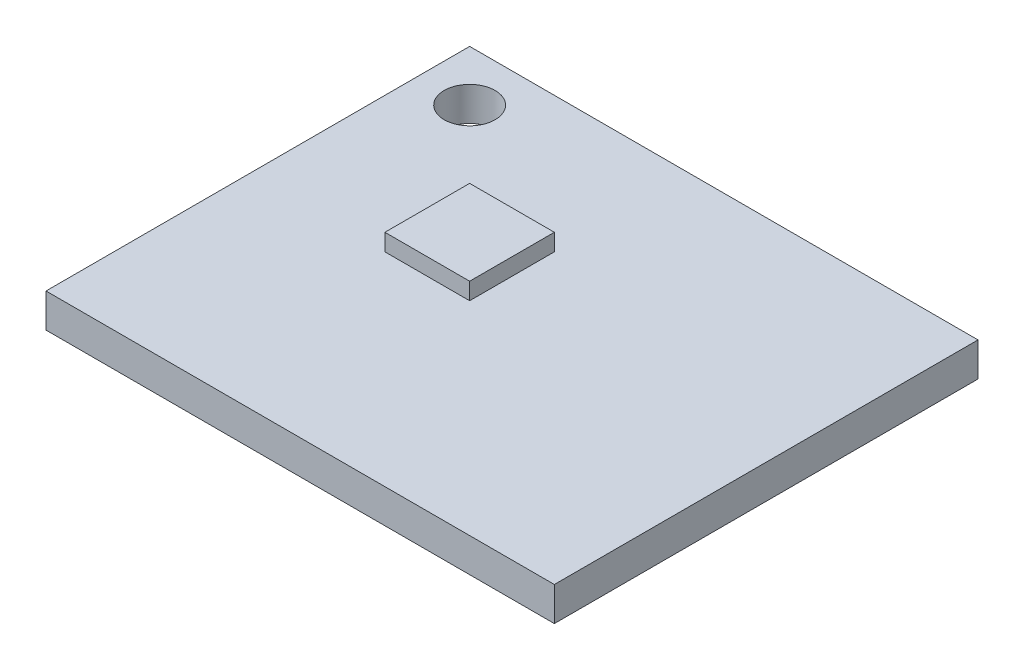
SolidWorks part; units mm, degrees
ref_plane "Front Plane" through (0, 0, 0) normal (0, 0, 1) x (1, 0, 0)
ref_plane "Top Plane" through (0, 0, 0) normal (0, 1, 0) x (1, 0, 0)
ref_plane "Right Plane" through (0, 0, 0) normal (1, 0, 0) x (0, 0, -1)
sketch "Sketch1" plane through (0, 0, 0) normal (0, 1, 0) x (1, 0, 0)
  line L1 (0, 0) -> (30, 0)
  line L2 (0, 0) -> (0, 25)
  line L3 (0, 25) -> (30, 25)
  line L4 (30, 0) -> (30, 25)
  dimension "D1" = 25
  dimension "D2" = 30
extrude "Boss-Extrude1" add sketch "Sketch1" along normal blind 2
sketch "Sketch2" plane through (0, 2, 0) normal (0, 1, 0) x (1, 0, 0)
  line L0 (0, 25) -> (0, 0) construction
  line L1 (8, 17) -> (13, 17)
  line L2 (8, 17) -> (8, 12)
  line L3 (8, 12) -> (13, 12)
  line L4 (13, 17) -> (13, 12)
  line L5 (30, 25) -> (0, 25) construction
  dimension "D1" = 8
  dimension "D2" = 8
  dimension "D3" = 5
  dimension "D4" = 5
extrude "Boss-Extrude2" add sketch "Sketch2" along normal blind 1
sketch "Sketch3" plane through (0, 2, 0) normal (0, 1, 0) x (1, 0, 0)
  line L0 (0, 25) -> (0, 0) construction
  line L1 (30, 25) -> (0, 25) construction
  circle A0 centre (3, 22) radius 1.5
  dimension "D1" = 3
  dimension "D2" = 3
  dimension "D3" = 3
extrude "Cut-Extrude1" cut sketch "Sketch3" against normal blind 4
